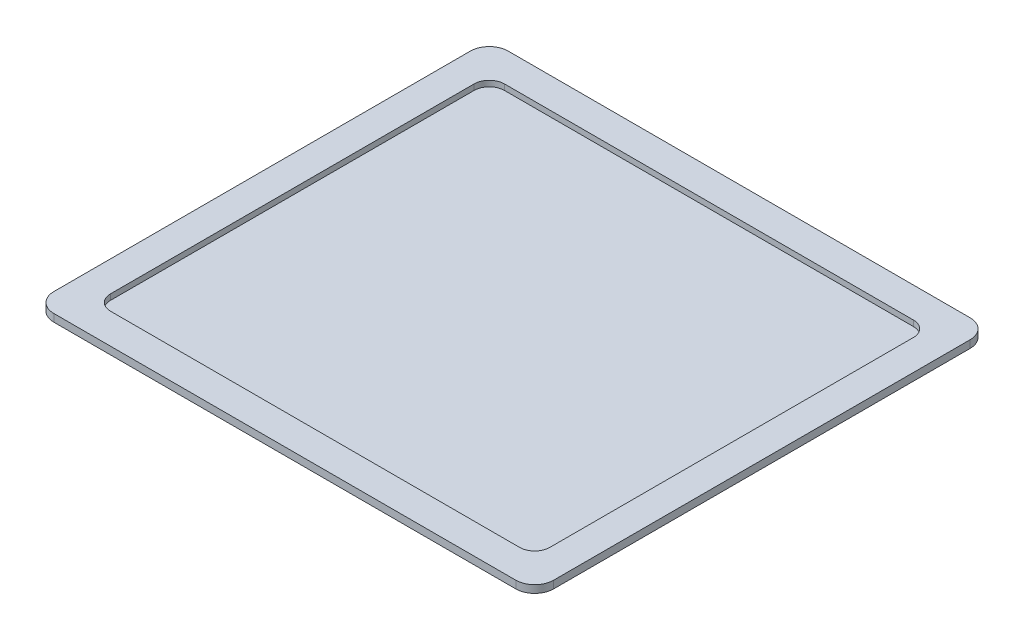
SolidWorks part; units mm, degrees
material "Acrílico (médio-alto impacto)"
ref_plane "Plano frontal" through (0, 0, 0) normal (0, 0, 1) x (1, 0, 0)
ref_plane "Plano superior" through (0, 0, 0) normal (0, 1, 0) x (1, 0, 0)
ref_plane "Plano direito" through (0, 0, 0) normal (1, 0, 0) x (0, 0, -1)
sketch "Esboço1" plane through (0, 0, 0) normal (0, 1, 0) x (1, 0, 0)
  line L1 (-305, -300) -> (305, -300)
  line L6 (-330, -275) -> (-330, 275)
  line L7 (-305, 300) -> (305, 300)
  line L8 (330, -275) -> (330, 275)
  line L9 (-330, -300) -> (330, 300) construction
  line L10 (-330, 300) -> (330, -300) construction
  line L11 (270, -260) -> (-270, -260)
  line L12 (290, -240) -> (290, 240)
  line L13 (270, 260) -> (-270, 260)
  line L14 (-290, -240) -> (-290, 240)
  line L15 (290, -260) -> (-290, 260) construction
  line L16 (290, 260) -> (-290, -260) construction
  arc A0 (305, -300) -> (330, -275) centre (305, -275) ccw
  arc A1 (305, 300) -> (330, 275) centre (305, 275) cw
  arc A2 (-330, 275) -> (-305, 300) centre (-305, 275) cw
  arc A3 (-305, -300) -> (-330, -275) centre (-305, -275) cw
  arc A4 (-270, -260) -> (-290, -240) centre (-270, -240) cw
  arc A5 (270, -260) -> (290, -240) centre (270, -240) ccw
  arc A6 (290, 240) -> (270, 260) centre (270, 240) ccw
  arc A7 (-270, 260) -> (-290, 240) centre (-270, 240) ccw
  point P0 (0, 0)
  point P5 (0, 0)
  dimension "D3" = 40
  dimension "D4" = 40
  dimension "D5" = 25
  dimension "D6" = 20
  dimension "D1" = 660
  dimension "D2" = 600
extrude "Ressalto-extrusão2" add sketch "Esboço1" along normal blind 10
sketch "Esboço2" plane through (0, 0, 0) normal (0, 1, 0) x (1, 0, 0)
  line L36 (300, -240) -> (300, 240)
  line L37 (-270, -270) -> (270, -270)
  line L38 (-300, 240) -> (-300, -240)
  line L39 (270, 270) -> (-270, 270)
  line L40 (300, -240) -> (300, 240)
  line L41 (-270, -270) -> (270, -270)
  line L42 (-300, 240) -> (-300, -240)
  line L43 (270, 270) -> (-270, 270)
  arc A36 (270, -270) -> (300, -240) centre (270, -240) ccw
  arc A37 (-300, -240) -> (-270, -270) centre (-270, -240) ccw
  arc A38 (-270, 270) -> (-300, 240) centre (-270, 240) ccw
  arc A39 (300, 240) -> (270, 270) centre (270, 240) ccw
  arc A40 (270, -270) -> (300, -240) centre (270, -240) ccw
  arc A41 (-300, -240) -> (-270, -270) centre (-270, -240) ccw
  arc A42 (-270, 270) -> (-300, 240) centre (-270, 240) ccw
  arc A43 (300, 240) -> (270, 270) centre (270, 240) ccw
  dimension "D1" = 10
extrude "Ressalto-extrusão3" add sketch "Esboço2" along normal mid plane 5
